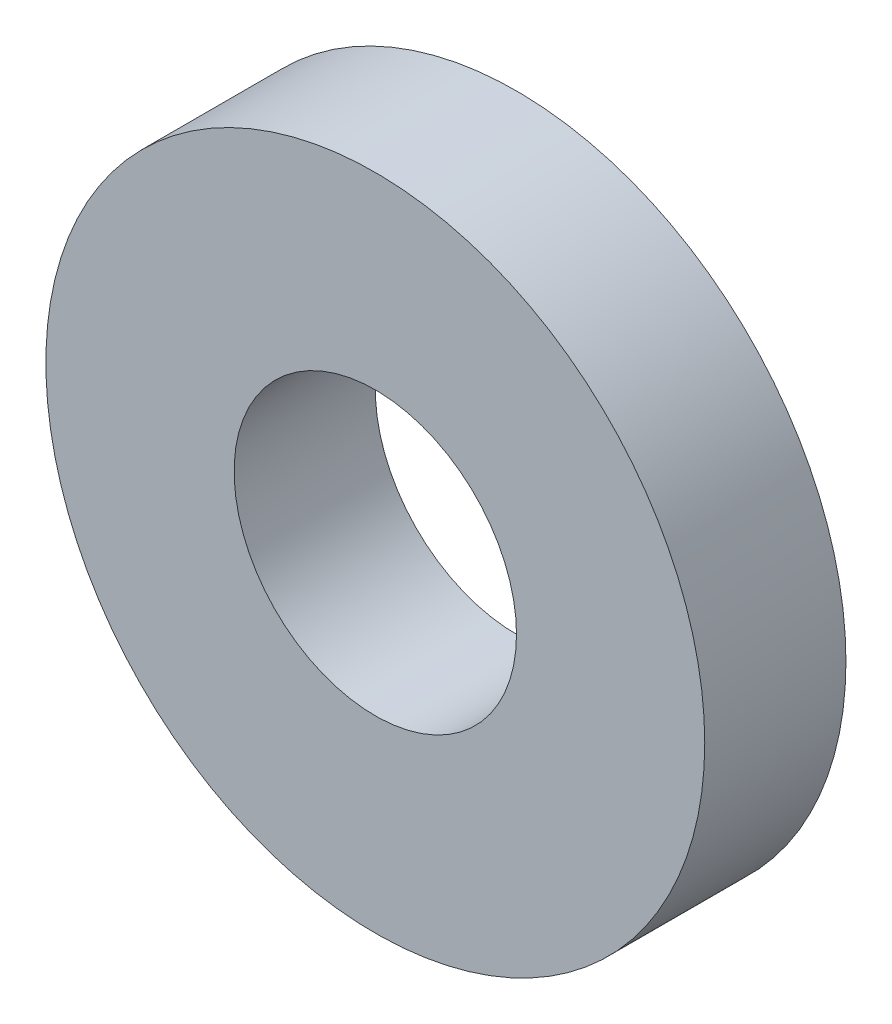
SolidWorks part; units mm, degrees
ref_plane "Plan de face" through (0, 0, 0) normal (0, 0, 1) x (1, 0, 0)
ref_plane "Plan de dessus" through (0, 0, 0) normal (0, 1, 0) x (1, 0, 0)
ref_plane "Plan de droite" through (0, 0, 0) normal (1, 0, 0) x (0, 0, -1)
sketch "Esquisse1" plane through (0, 0, 0) normal (0, 0, 1) x (1, 0, 0)
  circle A0 centre (0, 0) radius 7
  circle A1 centre (0, 0) radius 3
  dimension "D1" = 6
  dimension "D2" = 14
extrude "Boss.-Extru.1" add sketch "Esquisse1" along normal blind 3
